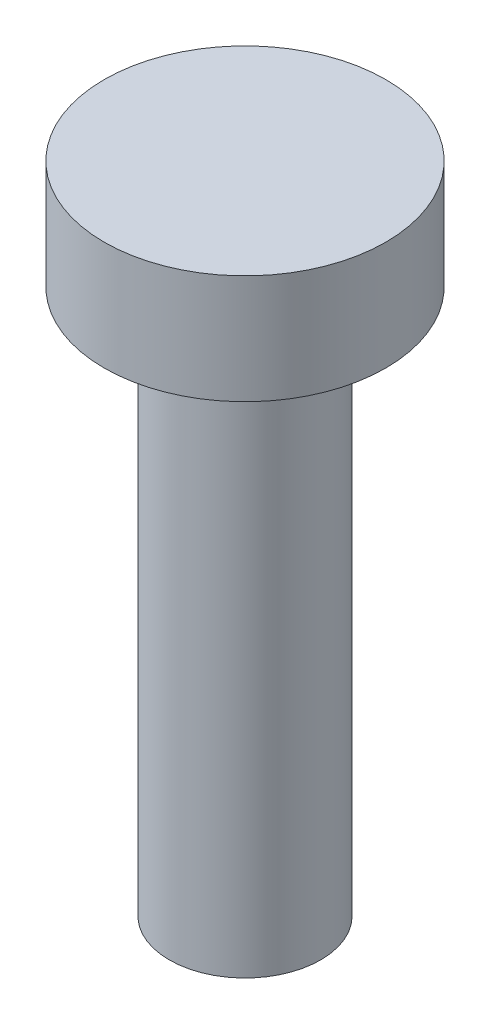
SolidWorks part; units mm, degrees
ref_plane "前视基准面" through (0, 0, 0) normal (0, 0, 1) x (1, 0, 0)
ref_plane "上视基准面" through (0, 0, 0) normal (0, 1, 0) x (1, 0, 0)
ref_plane "右视基准面" through (0, 0, 0) normal (1, 0, 0) x (0, 0, -1)
sketch "草图1" plane through (0, 0, 0) normal (0, 1, 0) x (1, 0, 0)
  circle A0 centre (0, 0) radius 2.5
  dimension "D1" = 5
extrude "凸台-拉伸1" add sketch "草图1" along normal blind 18
sketch "草图2" plane through (0, 18, 0) normal (0, 1, 0) x (1, 0, 0)
  circle A0 centre (0, 0) radius 4.65
  dimension "D1" = 9.3
extrude "凸台-拉伸2" add sketch "草图2" along normal blind 3.6
